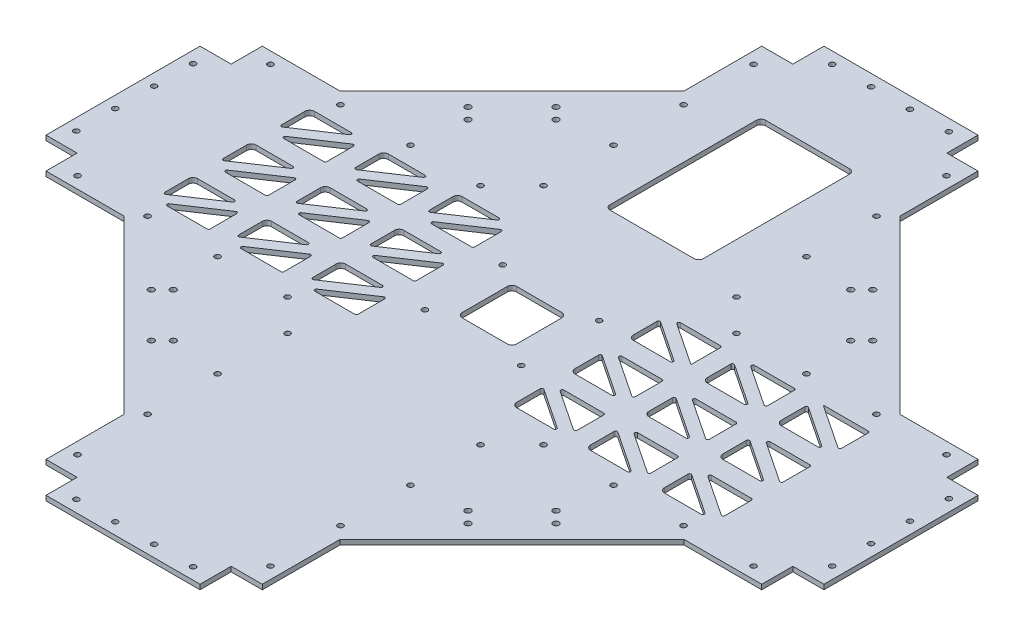
SolidWorks part; units mm, degrees
ref_plane "Front Plane" through (0, 0, 0) normal (0, 0, 1) x (1, 0, 0)
ref_plane "Top Plane" through (0, 0, 0) normal (0, 1, 0) x (1, 0, 0)
ref_plane "Right Plane" through (0, 0, 0) normal (1, 0, 0) x (0, 0, -1)
sketch "Sketch1" plane through (0, 0, 0) normal (0, 1, 0) x (1, 0, 0)
  line L0 (-250, 69.5) -> (250, -69.5) construction
  line L1 (-69.5, -250) -> (69.5, -250)
  line L2 (-69.5, -250) -> (-69.5, 250)
  line L3 (-69.5, 250) -> (69.5, 250)
  line L4 (69.5, -250) -> (69.5, 250)
  line L5 (69.5, 250) -> (-69.5, -250) construction
  line L6 (-69.5, 180) -> (-180, 69.5)
  line L7 (-250, -69.5) -> (250, -69.5)
  line L8 (-250, -69.5) -> (-250, 69.5)
  line L9 (-250, 69.5) -> (250, 69.5)
  line L10 (250, -69.5) -> (250, 69.5)
  line L11 (-180, -69.5) -> (-69.5, -180)
  line L12 (69.5, -180) -> (180, -69.5)
  line L13 (69.5, 180) -> (180, 69.5)
  point P0 (0, 0)
  point P6 (0, 0)
  point P11 (0, 0)
  point P12 (0, 0)
  point P21 (0, 0)
  dimension "D1" = 500
  dimension "D2" = 500
  dimension "D3" = 139
  dimension "D4" = 139
  dimension "D5" = 70
  dimension "D6" = 70
  dimension "D7" = 70
  dimension "D8" = 70
  dimension "D9" = 70
extrude "Boss-Extrude1" add sketch "Sketch1" along normal blind 3.125 contours L9 L8 L7 L2 | L9 L2 L7 L4 | L2 L9 L4 L3 | L7 L10 L9 L4 | L7 L2 L1 L4 | L6 L9 L2 | L7 L11 L2 | L4 L12 L7 | L13 L4 L9
sketch "Sketch2" plane through (0, 3.125, 0) normal (0, 1, 0) x (1, 0, 0)
  line L1 (-69.5, 250) -> (-49.5, 250)
  line L2 (-69.5, 250) -> (-69.5, 230)
  line L3 (-69.5, 230) -> (-49.5, 230)
  line L4 (-49.5, 250) -> (-49.5, 230)
  line L5 (-69.5, 250) -> (-49.5, 230) construction
  line L6 (-69.5, 230) -> (-49.5, 250) construction
  line L7 (69.5, 250) -> (49.5, 250)
  line L8 (69.5, 250) -> (69.5, 230)
  line L9 (69.5, 230) -> (49.5, 230)
  line L10 (49.5, 250) -> (49.5, 230)
  line L11 (69.5, 250) -> (49.5, 230) construction
  line L12 (69.5, 230) -> (49.5, 250) construction
  line L13 (250, 69.5) -> (230, 69.5)
  line L14 (250, 69.5) -> (250, 49.5)
  line L15 (250, 49.5) -> (230, 49.5)
  line L16 (230, 69.5) -> (230, 49.5)
  line L17 (250, 69.5) -> (230, 49.5) construction
  line L18 (250, 49.5) -> (230, 69.5) construction
  line L19 (250, -69.5) -> (230, -69.5)
  line L20 (250, -69.5) -> (250, -49.5)
  line L21 (250, -49.5) -> (230, -49.5)
  line L22 (230, -69.5) -> (230, -49.5)
  line L23 (250, -69.5) -> (230, -49.5) construction
  line L24 (250, -49.5) -> (230, -69.5) construction
  line L25 (69.5, -250) -> (49.5, -250)
  line L26 (69.5, -250) -> (69.5, -230)
  line L27 (69.5, -230) -> (49.5, -230)
  line L28 (49.5, -250) -> (49.5, -230)
  line L29 (69.5, -250) -> (49.5, -230) construction
  line L30 (69.5, -230) -> (49.5, -250) construction
  line L31 (-69.5, -250) -> (-49.5, -250)
  line L32 (-69.5, -250) -> (-69.5, -230)
  line L33 (-69.5, -230) -> (-49.5, -230)
  line L34 (-49.5, -250) -> (-49.5, -230)
  line L35 (-69.5, -250) -> (-49.5, -230) construction
  line L36 (-69.5, -230) -> (-49.5, -250) construction
  line L37 (-250, -69.5) -> (-230, -69.5)
  line L38 (-250, -69.5) -> (-250, -49.5)
  line L39 (-250, -49.5) -> (-230, -49.5)
  line L40 (-230, -69.5) -> (-230, -49.5)
  line L41 (-250, -69.5) -> (-230, -49.5) construction
  line L42 (-250, -49.5) -> (-230, -69.5) construction
  line L43 (-250, 69.5) -> (-230, 69.5)
  line L44 (-250, 69.5) -> (-250, 49.5)
  line L45 (-250, 49.5) -> (-230, 49.5)
  line L46 (-230, 69.5) -> (-230, 49.5)
  line L47 (-250, 69.5) -> (-230, 49.5) construction
  line L48 (-250, 49.5) -> (-230, 69.5) construction
  point P4 (-59.5, 240)
  point P10 (59.5, 240)
  point P17 (240, 59.5)
  point P22 (240, -59.5)
  point P28 (59.5, -240)
  point P34 (-59.5, -240)
  point P40 (-240, -59.5)
  point P46 (-240, 59.5)
  dimension "D1" = 20
  dimension "D2" = 20
extrude "Cut-Extrude1" cut sketch "Sketch2" against normal through all
sketch "Sketch3" plane through (0, 3.125, 0) normal (0, 1, 0) x (1, 0, 0)
  line L0 (-230, -49.5) -> (-250, -49.5) construction
  line L1 (-250, 49.5) -> (-235, 49.5) construction
  line L2 (-250, 49.5) -> (-250, -49.5) construction
  line L3 (-250, -49.5) -> (-235, -49.5) construction
  line L4 (-235, 49.5) -> (-235, -49.5) construction
  line L5 (-250, 49.5) -> (-235, -49.5) construction
  line L6 (-250, -49.5) -> (-235, 49.5) construction
  line L7 (-69.5, 180) -> (-69.5, 230) construction
  line L8 (-230, 69.5) -> (-69.5, 69.5) construction
  line L9 (-230, 69.5) -> (-230, 54.5) construction
  line L10 (-230, 54.5) -> (-69.5, 54.5) construction
  line L11 (-69.5, 69.5) -> (-69.5, 54.5) construction
  line L12 (-230, 69.5) -> (-69.5, 54.5) construction
  line L13 (-230, 54.5) -> (-69.5, 69.5) construction
  line L14 (49.5, 250) -> (49.5, 230) construction
  line L15 (-69.5, 230) -> (-54.5, 230) construction
  line L16 (-69.5, 230) -> (-69.5, 69.5) construction
  line L17 (-69.5, 69.5) -> (-54.5, 69.5) construction
  line L18 (-54.5, 230) -> (-54.5, 69.5) construction
  line L19 (-69.5, 230) -> (-54.5, 69.5) construction
  line L20 (-69.5, 69.5) -> (-54.5, 230) construction
  line L21 (-49.5, 250) -> (49.5, 250) construction
  line L22 (-49.5, 250) -> (-49.5, 235) construction
  line L23 (-49.5, 235) -> (49.5, 235) construction
  line L24 (49.5, 250) -> (49.5, 235) construction
  line L25 (-49.5, 250) -> (49.5, 235) construction
  line L26 (-49.5, 235) -> (49.5, 250) construction
  line L27 (-242.5, -37.5) -> (-242.5, -12.5) construction
  line L28 (69.5, 230) -> (54.5, 230) construction
  line L29 (69.5, 230) -> (69.5, 69.5) construction
  line L30 (69.5, 69.5) -> (54.5, 69.5) construction
  line L31 (54.5, 230) -> (54.5, 69.5) construction
  line L32 (69.5, 230) -> (54.5, 69.5) construction
  line L33 (69.5, 69.5) -> (54.5, 230) construction
  line L34 (230, 69.5) -> (69.5, 69.5) construction
  line L35 (230, 69.5) -> (230, 54.5) construction
  line L36 (230, 54.5) -> (69.5, 54.5) construction
  line L37 (69.5, 69.5) -> (69.5, 54.5) construction
  line L38 (230, 69.5) -> (69.5, 54.5) construction
  line L39 (230, 54.5) -> (69.5, 69.5) construction
  line L40 (250, 49.5) -> (235, 49.5) construction
  line L41 (250, 49.5) -> (250, -49.5) construction
  line L42 (250, -49.5) -> (235, -49.5) construction
  line L43 (235, 49.5) -> (235, -49.5) construction
  line L44 (250, 49.5) -> (235, -49.5) construction
  line L45 (250, -49.5) -> (235, 49.5) construction
  line L46 (-49.5, -250) -> (-49.5, -230) construction
  line L47 (230, -69.5) -> (69.5, -69.5) construction
  line L48 (230, -69.5) -> (230, -54.5) construction
  line L49 (230, -54.5) -> (69.5, -54.5) construction
  line L50 (69.5, -69.5) -> (69.5, -54.5) construction
  line L51 (230, -69.5) -> (69.5, -54.5) construction
  line L52 (230, -54.5) -> (69.5, -69.5) construction
  line L53 (69.5, -230) -> (54.5, -230) construction
  line L54 (69.5, -230) -> (69.5, -69.5) construction
  line L55 (69.5, -69.5) -> (54.5, -69.5) construction
  line L56 (54.5, -230) -> (54.5, -69.5) construction
  line L57 (69.5, -230) -> (54.5, -69.5) construction
  line L58 (69.5, -69.5) -> (54.5, -230) construction
  line L59 (49.5, -250) -> (-49.5, -250) construction
  line L60 (49.5, -250) -> (49.5, -235) construction
  line L61 (49.5, -235) -> (-49.5, -235) construction
  line L62 (-49.5, -250) -> (-49.5, -235) construction
  line L63 (49.5, -250) -> (-49.5, -235) construction
  line L64 (49.5, -235) -> (-49.5, -250) construction
  line L65 (-242.5, 49.5) -> (-242.5, 37.5) construction
  line L66 (-69.5, -230) -> (-54.5, -230) construction
  line L67 (-69.5, -230) -> (-69.5, -69.5) construction
  line L68 (-69.5, -69.5) -> (-54.5, -69.5) construction
  line L69 (-54.5, -230) -> (-54.5, -69.5) construction
  line L70 (-69.5, -230) -> (-54.5, -69.5) construction
  line L71 (-69.5, -69.5) -> (-54.5, -230) construction
  line L72 (-230, -69.5) -> (-69.5, -69.5) construction
  line L73 (-230, -69.5) -> (-230, -54.5) construction
  line L74 (-230, -54.5) -> (-69.5, -54.5) construction
  line L75 (-69.5, -69.5) -> (-69.5, -54.5) construction
  line L76 (-230, -69.5) -> (-69.5, -54.5) construction
  line L77 (-230, -54.5) -> (-69.5, -69.5) construction
  line L78 (-242.5, -49.5) -> (-242.5, -37.5) construction
  line L79 (250, -49.5) -> (230, -49.5) construction
  line L80 (-230, 62) -> (-217.25, 62) construction
  line L81 (-69.5, 62) -> (-82.25, 62) construction
  line L82 (-217.25, 62) -> (-172.25, 62) construction
  line L83 (-217.25, -62) -> (-172.25, -62) construction
  line L84 (-230, -62) -> (-217.25, -62) construction
  line L85 (-62, 82.25) -> (-62, 127.25) construction
  line L86 (-62, 69.5) -> (-62, 82.25) construction
  line L87 (-49.5, 242.5) -> (-36.75, 242.5) construction
  line L88 (-36.75, 242.5) -> (-11.75, 242.5) construction
  line L89 (0, 0) -> (69.5, 69.5) construction
  line L90 (62, 69.5) -> (62, 82.25) construction
  line L91 (62, 82.25) -> (62, 127.25) construction
  line L93 (31, -25) -> (-31, -25) construction
  line L94 (31, -25) -> (31, 25) construction
  line L95 (31, 25) -> (-31, 25) construction
  line L96 (-31, -25) -> (-31, 25) construction
  line L97 (31, -25) -> (-31, 25) construction
  line L98 (31, 25) -> (-31, -25) construction
  circle A0 centre (-242.5, -37.5) radius 1.75
  circle A1 centre (-242.5, -12.5) radius 1.75
  circle A2 centre (-242.5, 12.5) radius 1.75
  circle A3 centre (-242.5, 37.5) radius 1.75
  circle A4 centre (-217.25, 62) radius 1.75
  circle A5 centre (-172.25, 62) radius 1.75
  circle A6 centre (-127.25, 62) radius 1.75
  circle A7 centre (-82.25, 62) radius 1.75
  circle A8 centre (-217.25, -62) radius 1.75
  circle A9 centre (-172.25, -62) radius 1.75
  circle A10 centre (-127.25, -62) radius 1.75
  circle A11 centre (-82.25, -62) radius 1.75
  circle A12 centre (-62, 82.25) radius 1.75
  circle A13 centre (-62, 127.25) radius 1.75
  circle A14 centre (-62, 172.25) radius 1.75
  circle A15 centre (-62, 217.25) radius 1.75
  circle A16 centre (-36.75, 242.5) radius 1.75
  circle A17 centre (-11.75, 242.5) radius 1.75
  circle A18 centre (13.25, 242.5) radius 1.75
  circle A19 centre (38.25, 242.5) radius 1.75
  circle A20 centre (62, 82.25) radius 1.75
  circle A21 centre (62, 127.25) radius 1.75
  circle A22 centre (62, 172.25) radius 1.75
  circle A23 centre (62, 217.25) radius 1.75
  circle A24 centre (82.25, 62) radius 1.75
  circle A25 centre (127.25, 62) radius 1.75
  circle A26 centre (172.25, 62) radius 1.75
  circle A27 centre (217.25, 62) radius 1.75
  circle A28 centre (242.5, 38.25) radius 1.75
  circle A29 centre (242.5, 13.25) radius 1.75
  circle A30 centre (242.5, -11.75) radius 1.75
  circle A31 centre (242.5, -36.75) radius 1.75
  circle A32 centre (217.25, -62) radius 1.75
  circle A33 centre (172.25, -62) radius 1.75
  circle A34 centre (127.25, -62) radius 1.75
  circle A35 centre (82.25, -62) radius 1.75
  circle A36 centre (62, -82.25) radius 1.75
  circle A37 centre (62, -127.25) radius 1.75
  circle A38 centre (62, -172.25) radius 1.75
  circle A39 centre (62, -217.25) radius 1.75
  circle A40 centre (37.5, -242.5) radius 1.75
  circle A41 centre (12.5, -242.5) radius 1.75
  circle A42 centre (-12.5, -242.5) radius 1.75
  circle A43 centre (-37.5, -242.5) radius 1.75
  circle A44 centre (-62, -82.25) radius 1.75
  circle A45 centre (-62, -127.25) radius 1.75
  circle A46 centre (-62, -172.25) radius 1.75
  circle A47 centre (-62, -217.25) radius 1.75
  circle A48 centre (-31, 25) radius 1.75
  circle A49 centre (31, 25) radius 1.75
  circle A50 centre (31, -25) radius 1.75
  circle A51 centre (-31, -25) radius 1.75
  point P4 (-242.5, 0)
  point P12 (-149.75, 62)
  point P20 (-62, 149.75)
  point P26 (0, 242.5)
  point P34 (62, 149.75)
  point P39 (149.75, 62)
  point P45 (242.5, 0)
  point P53 (149.75, -62)
  point P58 (62, -149.75)
  point P64 (0, -242.5)
  point P72 (-62, -149.75)
  point P77 (-149.75, -62)
  dimension "D2" = 3.5
  dimension "D20" = 3.5
  dimension "D1" = 15
  dimension "D4" = 25
  dimension "D5" = 12
  dimension "D7" = 12.75
  dimension "D8" = 45
  dimension "D10" = 45
  dimension "D11" = 4
  dimension "D12" = 45
  dimension "D13" = 12.75
  dimension "D15" = 25
  dimension "D17" = 45
  dimension "D18" = 62
  dimension "D19" = 50
  dimension "D3" = 4
  dimension "D6" = 4
  dimension "D9" = 4
  dimension "D14" = 4
  dimension "D16" = 4
extrude "Cut-Extrude2" cut sketch "Sketch3" against normal through all
sketch "Sketch4" plane through (0, 3.125, 0) normal (0, 1, 0) x (1, 0, 0)
  line L0 (-130.0533, 101.769) -> (-101.769, 130.0533) construction
  line L1 (-101.769, 130.0533) -> (-94.698, 122.9822) construction
  line L2 (-94.698, 122.9822) -> (-122.9822, 94.698) construction
  line L3 (-122.9822, 94.698) -> (-130.0533, 101.769) construction
  line L4 (-124.75, 124.75) -> (-132.4447, 132.4447) construction
  line L5 (-69.5, 180) -> (-180, 69.5) construction
  line L6 (-130.0533, 101.769) -> (-94.698, 122.9822) construction
  line L7 (-115.9112, 115.9112) -> (-108.8401, 108.8401) construction
  line L8 (0, 0) -> (-94.698, 122.9822) construction
  circle A0 centre (-101.769, 130.0533) radius 1.9
  circle A1 centre (-94.698, 122.9822) radius 1.9
  circle A2 centre (-130.0533, 101.769) radius 1.9
  circle A3 centre (-122.9822, 94.698) radius 1.9
  circle A4 centre (130.0533, 101.769) radius 1.9
  circle A5 centre (122.9822, 94.698) radius 1.9
  circle A6 centre (101.769, 130.0533) radius 1.9
  circle A7 centre (94.698, 122.9822) radius 1.9
  circle A8 centre (101.769, -130.0533) radius 1.9
  circle A9 centre (94.698, -122.9822) radius 1.9
  circle A10 centre (130.0533, -101.769) radius 1.9
  circle A11 centre (122.9822, -94.698) radius 1.9
  circle A12 centre (-130.0533, -101.769) radius 1.9
  circle A13 centre (-122.9822, -94.698) radius 1.9
  circle A14 centre (-101.769, -130.0533) radius 1.9
  circle A15 centre (-94.698, -122.9822) radius 1.9
  point P3 (0, 0)
  point P14 (0, 0)
  point P15 (0, 0)
  point P41 (0, 0)
  point P43 (0, 0)
  point P44 (-94.698, 122.9822)
  dimension "D3" = 3.8
  dimension "D1" = 40
  dimension "D2" = 10
  dimension "D4" = 12.5
  dimension "D5" = 4
extrude "Cut-Extrude3" cut sketch "Sketch4" against normal through all
sketch "Sketch5" plane through (0, 3.125, 0) normal (0, 1, 0) x (1, 0, 0)
  line L0 (-162.5, 37.5) -> (-162.5, 0) construction
  line L1 (-17.5, -17.5) -> (17.5, -17.5)
  line L2 (-17.5, -17.5) -> (-17.5, 17.5)
  line L3 (-17.5, 17.5) -> (17.5, 17.5)
  line L4 (17.5, -17.5) -> (17.5, 17.5)
  line L5 (-17.5, -17.5) -> (17.5, 17.5) construction
  line L6 (-17.5, 17.5) -> (17.5, -17.5) construction
  line L7 (-180, 50) -> (-50, 50) construction
  line L8 (-180, 50) -> (-180, -50) construction
  line L9 (-180, -50) -> (-50, -50) construction
  line L10 (-50, 50) -> (-50, -50) construction
  line L11 (-132.5, 50) -> (-97.5, 50) construction
  line L12 (-132.5, 50) -> (-132.5, 25) construction
  line L17 (0, 0) -> (0, 61.8928) construction
  line L18 (50, 7.5) -> (80, -12.5)
  line L19 (-180, 50) -> (-145, 50) construction
  line L20 (-180, 50) -> (-180, 25) construction
  line L21 (-180, 25) -> (-145, 25) construction
  line L22 (-145, 50) -> (-145, 25) construction
  line L23 (-180, 50) -> (-145, 25) construction
  line L24 (-180, 25) -> (-145, 50) construction
  line L25 (-180, 12.5) -> (-145, 12.5) construction
  line L26 (-180, 12.5) -> (-180, -12.5) construction
  line L27 (-180, -12.5) -> (-145, -12.5) construction
  line L28 (-145, 12.5) -> (-145, -12.5) construction
  line L29 (-180, 12.5) -> (-145, -12.5) construction
  line L30 (-180, -12.5) -> (-145, 12.5) construction
  line L31 (-180, -25) -> (-145, -25) construction
  line L32 (-180, -25) -> (-180, -50) construction
  line L33 (-180, -50) -> (-145, -50) construction
  line L34 (-145, -25) -> (-145, -50) construction
  line L35 (-180, -25) -> (-145, -50) construction
  line L36 (-180, -50) -> (-145, -25) construction
  line L37 (-132.5, 25) -> (-97.5, 25) construction
  line L38 (-97.5, 50) -> (-97.5, 25) construction
  line L39 (-132.5, 50) -> (-97.5, 25) construction
  line L40 (-132.5, 25) -> (-97.5, 50) construction
  line L41 (-50, 50) -> (-85, 50) construction
  line L42 (-50, 50) -> (-50, 25) construction
  line L43 (-50, 25) -> (-85, 25) construction
  line L44 (-85, 50) -> (-85, 25) construction
  line L45 (-50, 50) -> (-85, 25) construction
  line L46 (-50, 25) -> (-85, 50) construction
  line L47 (-132.5, 12.5) -> (-97.5, 12.5) construction
  line L48 (-132.5, 12.5) -> (-132.5, -12.5) construction
  line L49 (-132.5, -12.5) -> (-97.5, -12.5) construction
  line L50 (-97.5, 12.5) -> (-97.5, -12.5) construction
  line L51 (-132.5, 12.5) -> (-97.5, -12.5) construction
  line L52 (-132.5, -12.5) -> (-97.5, 12.5) construction
  line L53 (-132.5, -25) -> (-97.5, -25) construction
  line L54 (-132.5, -25) -> (-132.5, -50) construction
  line L55 (-132.5, -50) -> (-97.5, -50) construction
  line L56 (-97.5, -25) -> (-97.5, -50) construction
  line L57 (-132.5, -25) -> (-97.5, -50) construction
  line L58 (-132.5, -50) -> (-97.5, -25) construction
  line L59 (-85, 12.5) -> (-50, 12.5) construction
  line L60 (-85, 12.5) -> (-85, -12.5) construction
  line L61 (-85, -12.5) -> (-50, -12.5) construction
  line L62 (-50, 12.5) -> (-50, -12.5) construction
  line L63 (-85, 12.5) -> (-50, -12.5) construction
  line L64 (-85, -12.5) -> (-50, 12.5) construction
  line L65 (-85, -25) -> (-50, -25) construction
  line L66 (-85, -25) -> (-85, -50) construction
  line L67 (-85, -50) -> (-50, -50) construction
  line L68 (-50, -25) -> (-50, -50) construction
  line L69 (-85, -25) -> (-50, -50) construction
  line L70 (-85, -50) -> (-50, -25) construction
  line L71 (-162.5, 0) -> (-162.5, -37.5) construction
  line L72 (-162.5, 37.5) -> (-115, 37.5) construction
  line L73 (-115, 37.5) -> (-67.5, 37.5) construction
  line L74 (-115, 37.5) -> (-115, 0) construction
  line L75 (-115, 0) -> (-115, -37.5) construction
  line L76 (-67.5, 37.5) -> (-67.5, 0) construction
  line L77 (-67.5, 0) -> (-67.5, -37.5) construction
  line L78 (-250, -49.5) -> (-250, 49.5) construction
  line L79 (-180, 50) -> (-180, 30)
  line L80 (-180, 30) -> (-150, 50)
  line L81 (-150, 50) -> (-180, 50)
  line L82 (-145, 25) -> (-145, 45)
  line L83 (-145, 45) -> (-175, 25)
  line L84 (-175, 25) -> (-145, 25)
  line L85 (-102.5, 50) -> (-132.5, 50)
  line L86 (-132.5, 50) -> (-132.5, 30)
  line L87 (-132.5, 30) -> (-102.5, 50)
  line L88 (-127.5, 25) -> (-97.5, 25)
  line L89 (-97.5, 25) -> (-97.5, 45)
  line L90 (-97.5, 45) -> (-127.5, 25)
  line L91 (-55, 50) -> (-85, 50)
  line L92 (-85, 50) -> (-85, 30)
  line L93 (-85, 30) -> (-55, 50)
  line L94 (-80, 25) -> (-50, 25)
  line L95 (-50, 25) -> (-50, 45)
  line L96 (-50, 45) -> (-80, 25)
  line L97 (-102.5, 12.5) -> (-132.5, 12.5)
  line L98 (-132.5, 12.5) -> (-132.5, -7.5)
  line L99 (-132.5, -7.5) -> (-102.5, 12.5)
  line L100 (-127.5, -12.5) -> (-97.5, -12.5)
  line L101 (-97.5, -12.5) -> (-97.5, 7.5)
  line L102 (-97.5, 7.5) -> (-127.5, -12.5)
  line L103 (-55, 12.5) -> (-85, 12.5)
  line L104 (-85, 12.5) -> (-85, -7.5)
  line L105 (-85, -7.5) -> (-55, 12.5)
  line L106 (-80, -12.5) -> (-50, -12.5)
  line L107 (-50, -12.5) -> (-50, 7.5)
  line L108 (-50, 7.5) -> (-80, -12.5)
  line L109 (-102.5, -25) -> (-132.5, -25)
  line L110 (-132.5, -25) -> (-132.5, -45)
  line L111 (-132.5, -45) -> (-102.5, -25)
  line L112 (-127.5, -50) -> (-97.5, -50)
  line L113 (-97.5, -50) -> (-97.5, -30)
  line L114 (-97.5, -30) -> (-127.5, -50)
  line L115 (-55, -25) -> (-85, -25)
  line L116 (-85, -25) -> (-85, -45)
  line L117 (-85, -45) -> (-55, -25)
  line L118 (-80, -50) -> (-50, -50)
  line L119 (-50, -50) -> (-50, -30)
  line L120 (-50, -30) -> (-80, -50)
  line L121 (-150, 12.5) -> (-180, 12.5)
  line L122 (-180, 12.5) -> (-180, -7.5)
  line L123 (-180, -7.5) -> (-150, 12.5)
  line L124 (-175, -12.5) -> (-145, -12.5)
  line L125 (-145, -12.5) -> (-145, 7.5)
  line L126 (-145, 7.5) -> (-175, -12.5)
  line L127 (-150, -25) -> (-180, -25)
  line L128 (-180, -25) -> (-180, -45)
  line L129 (-180, -45) -> (-150, -25)
  line L130 (-175, -50) -> (-145, -50)
  line L131 (-145, -50) -> (-145, -30)
  line L132 (-145, -30) -> (-175, -50)
  line L133 (-150, 50) -> (-102.5, 50) construction
  line L134 (-150, 50) -> (-150, 12.5) construction
  line L135 (50, -12.5) -> (50, 7.5)
  line L136 (80, -12.5) -> (50, -12.5)
  line L137 (85, -7.5) -> (55, 12.5)
  line L138 (85, 12.5) -> (85, -7.5)
  line L139 (55, 12.5) -> (85, 12.5)
  line L140 (50, 45) -> (80, 25)
  line L141 (50, 25) -> (50, 45)
  line L142 (80, 25) -> (50, 25)
  line L143 (85, 30) -> (55, 50)
  line L144 (85, 50) -> (85, 30)
  line L145 (55, 50) -> (85, 50)
  line L146 (97.5, 7.5) -> (127.5, -12.5)
  line L147 (97.5, -12.5) -> (97.5, 7.5)
  line L148 (127.5, -12.5) -> (97.5, -12.5)
  line L149 (132.5, -7.5) -> (102.5, 12.5)
  line L150 (132.5, 12.5) -> (132.5, -7.5)
  line L151 (102.5, 12.5) -> (132.5, 12.5)
  line L152 (97.5, 45) -> (127.5, 25)
  line L153 (97.5, 25) -> (97.5, 45)
  line L154 (127.5, 25) -> (97.5, 25)
  line L155 (132.5, 30) -> (102.5, 50)
  line L156 (132.5, 50) -> (132.5, 30)
  line L157 (102.5, 50) -> (132.5, 50)
  line L158 (145, 45) -> (175, 25)
  line L159 (145, 25) -> (145, 45)
  line L160 (175, 25) -> (145, 25)
  line L161 (180, 30) -> (150, 50)
  line L162 (180, 50) -> (180, 30)
  line L163 (150, 50) -> (180, 50)
  line L164 (180, -7.5) -> (150, 12.5)
  line L165 (180, 12.5) -> (180, -7.5)
  line L166 (150, 12.5) -> (180, 12.5)
  line L167 (145, 7.5) -> (175, -12.5)
  line L168 (145, -12.5) -> (145, 7.5)
  line L169 (175, -12.5) -> (145, -12.5)
  line L170 (180, -45) -> (150, -25)
  line L171 (180, -25) -> (180, -45)
  line L172 (150, -25) -> (180, -25)
  line L173 (145, -30) -> (175, -50)
  line L174 (145, -50) -> (145, -30)
  line L175 (175, -50) -> (145, -50)
  line L176 (132.5, -45) -> (102.5, -25)
  line L177 (132.5, -25) -> (132.5, -45)
  line L178 (102.5, -25) -> (132.5, -25)
  line L179 (97.5, -30) -> (127.5, -50)
  line L180 (97.5, -50) -> (97.5, -30)
  line L181 (127.5, -50) -> (97.5, -50)
  line L182 (85, -45) -> (55, -25)
  line L183 (85, -25) -> (85, -45)
  line L184 (55, -25) -> (85, -25)
  line L185 (50, -30) -> (80, -50)
  line L186 (50, -50) -> (50, -30)
  line L187 (80, -50) -> (50, -50)
  line L188 (-49.5, 250) -> (49.5, 250) construction
  line L189 (-30, 90) -> (30, 90)
  line L190 (-30, 90) -> (-30, 190)
  line L191 (-30, 190) -> (30, 190)
  line L192 (30, 90) -> (30, 190)
  line L193 (-30, 90) -> (30, 190) construction
  line L194 (-30, 190) -> (30, 90) construction
  point P0 (0, 0)
  point P21 (-162.5, 37.5)
  point P24 (-162.5, 0)
  point P28 (-162.5, -37.5)
  point P33 (-115, 37.5)
  point P37 (-67.5, 37.5)
  point P42 (-115, 0)
  point P47 (-115, -37.5)
  point P52 (-67.5, 0)
  point P57 (-67.5, -37.5)
  point P173 (0, 140)
  point P180 (0, 0)
  point P181 (0, 0)
  dimension "D1" = 35
  dimension "D2" = 35
  dimension "D3" = 35
  dimension "D4" = 130
  dimension "D5" = 135
  dimension "D6" = 25
  dimension "D7" = 100
  dimension "D8" = 20
  dimension "D9" = 30
  dimension "D10" = 3
  dimension "D12" = 47.5
  dimension "D13" = 37.5
  dimension "D14" = 60
  dimension "D15" = 100
  dimension "D16" = 60
  dimension "D11" = 3
extrude "Cut-Extrude4" cut sketch "Sketch5" against normal through all
fillet "Fillet1" radius 3 26 edges at (145, 1.5625, -25) (97.5, 1.5625, -25) (50, 1.5625, -25) (145, 1.5625, 12.5) (97.5, 1.5625, 12.5) (50, 1.5625, 12.5) (50, 1.5625, 50) (97.5, 1.5625, 50) (145, 1.5625, 50) (-17.5, 1.5625, 17.5) (17.5, 1.5625, 17.5) (17.5, 1.5625, -17.5) (-17.5, 1.5625, -17.5) (-85, 1.5625, 25) (-132.5, 1.5625, 25) (-132.5, 1.5625, -12.5) (-85, 1.5625, -12.5) (-85, 1.5625, -50) (-132.5, 1.5625, -50) (-180, 1.5625, 25) (-180, 1.5625, -12.5) (-180, 1.5625, -50) (-30, 1.5625, -90) (30, 1.5625, -90) (30, 1.5625, -190) (-30, 1.5625, -190)
fillet "Fillet2" radius 1 88 edges at (175, 1.5625, 12.5) (175, 1.5625, -25) (127.5, 1.5625, -25) (127.5, 1.5625, 12.5) (80, 1.5625, -25) (80, 1.5625, 12.5) (80, 1.5625, 50) (127.5, 1.5625, 50) (-150, 1.5625, 25) (-102.5, 1.5625, 25) (-55, 1.5625, 25) (-55, 1.5625, -12.5) (-102.5, 1.5625, -12.5) (-150, 1.5625, -12.5) (-55, 1.5625, -50) (-102.5, 1.5625, -50) (-150, 1.5625, -50) (145, 1.5625, -7.5) (145, 1.5625, -45) (97.5, 1.5625, -45) (97.5, 1.5625, -7.5) (97.5, 1.5625, 30) (50, 1.5625, 30) (50, 1.5625, -7.5) (50, 1.5625, -45) (-85, 1.5625, 45) (-85, 1.5625, 7.5) (-85, 1.5625, -30) (-132.5, 1.5625, 45) (-132.5, 1.5625, 7.5) (-132.5, 1.5625, -30) (-180, 1.5625, -30) (-180, 1.5625, 7.5) (-180, 1.5625, 45) (-145, 1.5625, 30) (-145, 1.5625, -7.5) (-145, 1.5625, -45) (-97.5, 1.5625, 30) (-97.5, 1.5625, -7.5) (-97.5, 1.5625, -45) (-50, 1.5625, 30) (-50, 1.5625, -7.5) (-50, 1.5625, -45) (85, 1.5625, 25) (85, 1.5625, -12.5) (85, 1.5625, -50) (132.5, 1.5625, 25) (132.5, 1.5625, -12.5) (132.5, 1.5625, -50) (180, 1.5625, 25) (180, 1.5625, -12.5) (180, 1.5625, -50) (-145, 1.5625, -25) (-97.5, 1.5625, -25) (-50, 1.5625, -25) (-97.5, 1.5625, 12.5) (-145, 1.5625, 50) (-97.5, 1.5625, 50) (-50, 1.5625, 12.5) (-50, 1.5625, 50) (85, 1.5625, 7.5) (85, 1.5625, 45) (132.5, 1.5625, 45) (132.5, 1.5625, 7.5) (132.5, 1.5625, -30) (180, 1.5625, -30) (180, 1.5625, 7.5) (180, 1.5625, 45) (145, 1.5625, 30) (175, 1.5625, 50) (-145, 1.5625, 12.5) (-175, 1.5625, -25) (-127.5, 1.5625, -25) (-80, 1.5625, -25) (-175, 1.5625, 12.5) (-127.5, 1.5625, 12.5) (-80, 1.5625, 12.5) (-175, 1.5625, 50) (-127.5, 1.5625, 50) (-80, 1.5625, 50) (150, 1.5625, -12.5) (102.5, 1.5625, -12.5) (102.5, 1.5625, -50) (55, 1.5625, -50) (150, 1.5625, 25) (102.5, 1.5625, 25) (55, 1.5625, -12.5) (55, 1.5625, 25)
